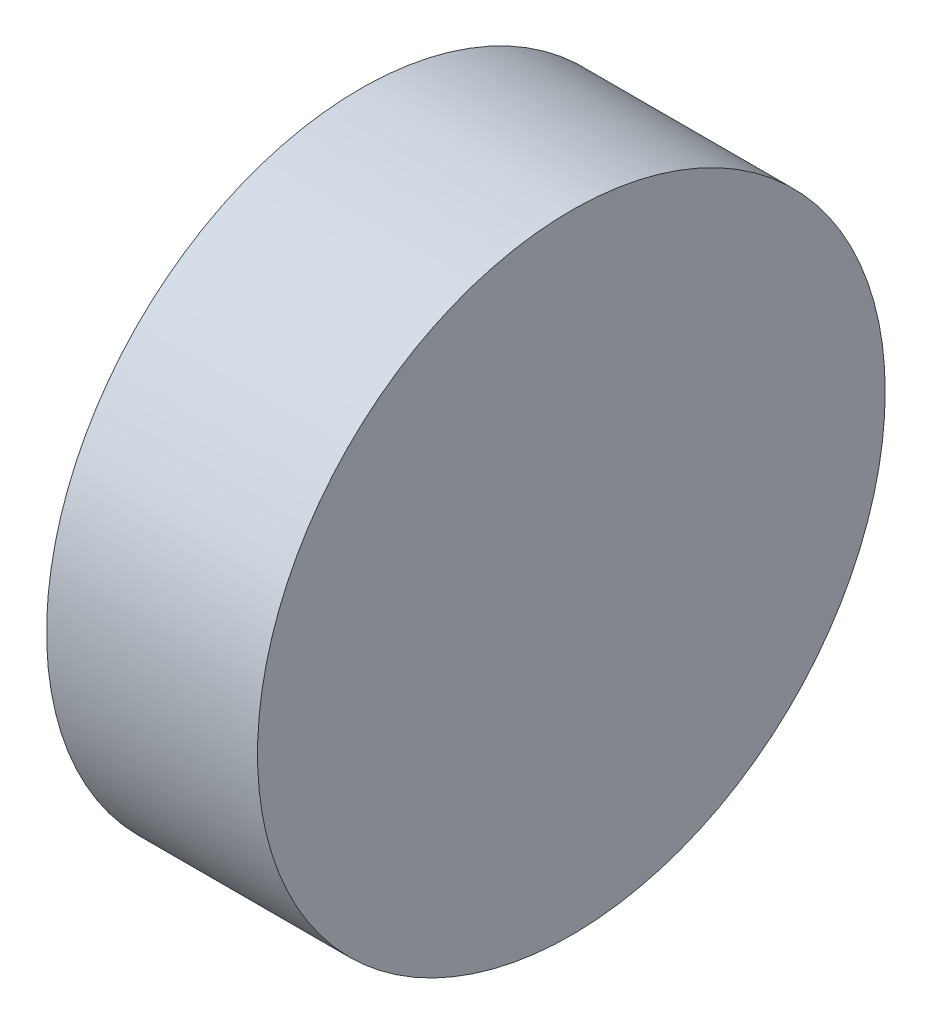
SolidWorks part; units mm, degrees
ref_plane "Front Plane" through (0, 0, 0) normal (0, 0, 1) x (1, 0, 0)
ref_plane "Top Plane" through (0, 0, 0) normal (0, 1, 0) x (1, 0, 0)
ref_plane "Right Plane" through (0, 0, 0) normal (1, 0, 0) x (0, 0, -1)
sketch "Sketch3" plane through (0, 0, 0) normal (1, 0, 0) x (0, 0, -1)
  circle A0 centre (0, 0) radius 6.25
  dimension "D1" = 12.5
extrude "Boss-Extrude1" add sketch "Sketch3" along normal blind 4.2
